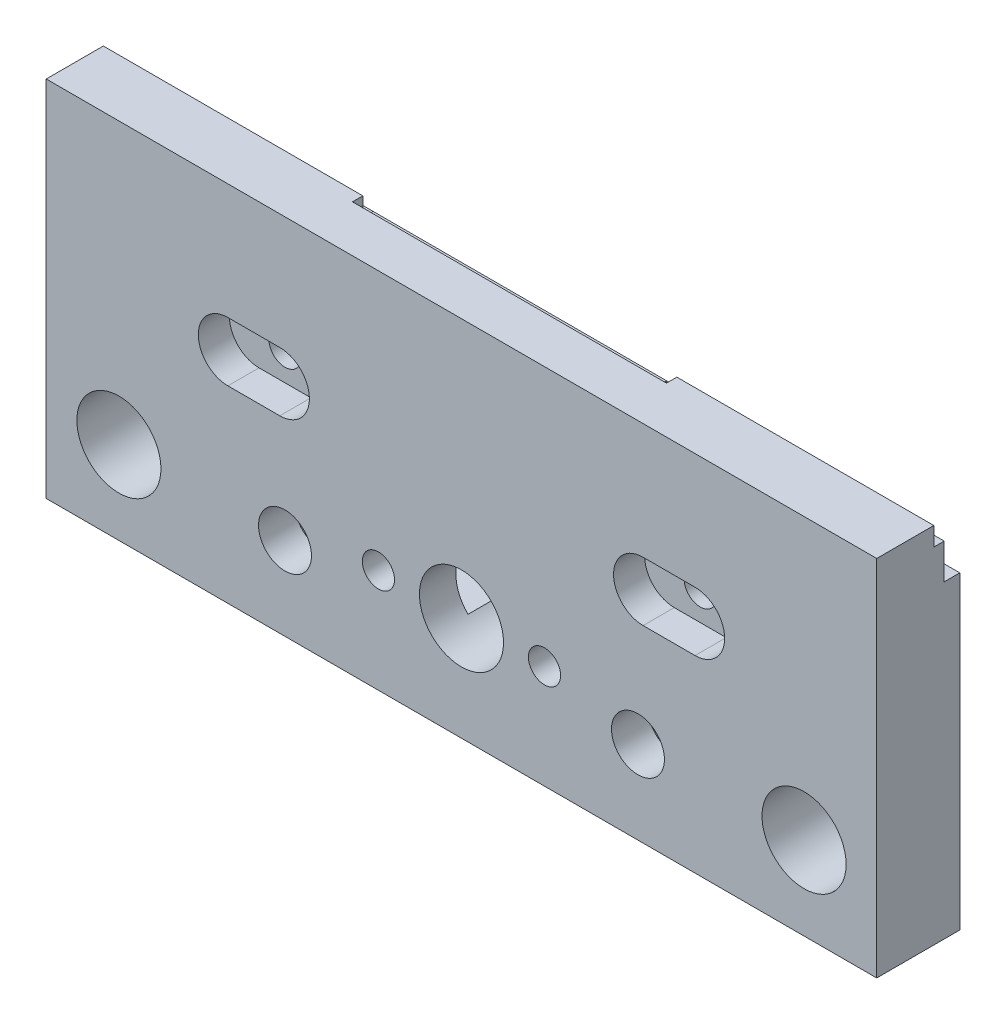
SolidWorks part; units mm, degrees
ref_plane "前视基准面" through (0, 0, 0) normal (0, 0, 1) x (1, 0, 0)
ref_plane "上视基准面" through (0, 0, 0) normal (0, 1, 0) x (1, 0, 0)
ref_plane "右视基准面" through (0, 0, 0) normal (1, 0, 0) x (0, 0, -1)
sketch "前视图草图" plane through (0, 0, 0) normal (0, 0, 1) x (1, 0, 0)
  line L0 (0, 0) -> (44.4821, 0) construction
  line L1 (0, 0) -> (0, 28.3185) construction
sketch "草图2" plane through (0, 0, 0) normal (0, 0, 1) x (1, 0, 0)
  line L0 (0, 0) -> (80, 0)
  line L1 (-200000, 0) -> (200044.4821, 0) construction
  line L2 (80, 0) -> (80, 35)
  line L3 (80, 35) -> (0, 35)
  line L4 (0, -200000) -> (0, 200028.3185) construction
  line L5 (0, 35) -> (0, 0)
  circle A0 centre (7, 8) radius 4.05
  circle A1 centre (40, 10) radius 4.05
  circle A2 centre (73, 8) radius 4.05
  dimension "D3" = 8
  dimension "D5" = 10
  dimension "D9" = 8.1
  dimension "D10" = 8.1
  dimension "D11" = 8.1
  dimension "D1" = 35
  dimension "D2" = 80
  dimension "D4" = 7
  dimension "D6" = 7
  dimension "D7" = 8
  dimension "D8" = 40
extrude "凸台-拉伸1" add sketch "草图2" along normal blind 8
sketch "草图3" plane through (0, 0, 8) normal (0, 0, 1) x (1, 0, 0)
  line L0 (16.088, 8) -> (31.4805, 8) construction
  line L1 (7, 8) -> (7, 16.8386) construction
  line L2 (73, 8) -> (73, 16.5917) construction
  line L4 (-200000, 0) -> (200044.4821, 0) construction
  circle A2 centre (23, 8) radius 2.55
  circle A3 centre (57, 8) radius 2.55
  dimension "D4" = 5.1
  dimension "D5" = 5.1
  dimension "D1" = 8
  dimension "D2" = 16
  dimension "D3" = 16
extrude "切除-拉伸1" cut sketch "草图3" against normal through all
sketch "草图4" plane through (80, 0, 0) normal (1, 0, 0) x (0, 0, -1)
  line L1 (0, -200000) -> (0, 200028.3185) construction
  line L2 (-1.5, 33.2) -> (-2.5, 33.2)
  line L3 (-2.5, 33.2) -> (-2.5, 35)
  line L4 (-8, 35) -> (0, 35) construction
  line L5 (-2.5, 35) -> (0, 35)
  line L6 (-1.5, 33.2) -> (-1.5, 29.8)
  line L7 (-1.5, 29.8) -> (0, 29.8)
  line L8 (0, 29.8) -> (0, 35)
  dimension "D1" = 3.4
  dimension "D2" = 2.5
  dimension "D3" = 1.5
  dimension "D4" = 1.8
extrude "切除-拉伸2" cut sketch "草图4" against normal through all
sketch "草图5" plane through (0, 0, 8) normal (0, 0, 1) x (1, 0, 0)
  line L0 (40, 10) -> (56.5376, 10) construction
  circle A0 centre (40, 10) radius 8 construction
  circle A1 centre (48, 10) radius 1.55
  circle A2 centre (32, 10) radius 1.55
  dimension "D1" = 3.1
  dimension "D2" = 3.1
  dimension "D3" = 16
extrude "切除-拉伸3" cut sketch "草图5" against normal through all
sketch "草图7" plane through (0, 0, 0) normal (0, 0, -1) x (-1, 0, 0)
  line L0 (-40, 12) -> (-40, -8.3696) construction
  line L1 (-23, 10) -> (-23, -2.3368) construction
  line L2 (200000, 0) -> (-200044.4821, 0) construction
  line L6 (-27.05, 10) -> (-27.05, 2.5)
  line L7 (-29.55, 0) -> (-16.45, 0)
  line L8 (-18.95, 2.5) -> (-18.95, 10)
  line L9 (-23, 8) -> (-23, 15.9045) construction
  line L13 (0, -200000) -> (0, 200028.3185) construction
  line L14 (-57, 8) -> (-57, 15.9045) construction
  line L15 (-57, 10) -> (-57, -2.3368) construction
  line L16 (-61.05, 2.5) -> (-61.05, 10)
  line L17 (-50.45, 0) -> (-63.55, 0)
  line L18 (-52.95, 10) -> (-52.95, 2.5)
  arc A1 (-18.95, 10) -> (-27.05, 10) centre (-23, 10) ccw
  arc A4 (-29.55, 0) -> (-27.05, 2.5) centre (-29.55, 2.5) ccw
  arc A5 (-18.95, 2.5) -> (-16.45, 0) centre (-16.45, 2.5) ccw
  arc A7 (-61.05, 2.5) -> (-63.55, 0) centre (-63.55, 2.5) cw
  arc A8 (-50.45, 0) -> (-52.95, 2.5) centre (-50.45, 2.5) cw
  arc A9 (-61.05, 10) -> (-52.95, 10) centre (-57, 10) cw
  dimension "D1" = 40
  dimension "D4" = 8.1
  dimension "D7" = 2.5
  dimension "D8" = 2.5
  dimension "D3" = 10
extrude "切除-拉伸4" cut sketch "草图7" against normal blind 4.5
sketch "草图8" plane through (0, 0, 0) normal (0, 0, -1) x (-1, 0, 0)
  line L0 (-40, 10) -> (-57.3165, 10) construction
  line L1 (-40, 20) -> (-40, 35.6562) construction
  line L2 (-30.5, 12.85) -> (-49.5, 12.85)
  line L3 (-49.5, 7.15) -> (-30.5, 7.15)
  line L4 (200000, 0) -> (-200044.4821, 0) construction
  arc A0 (-30.5, 7.15) -> (-30.5, 12.85) centre (-30.5, 10) ccw
  arc A1 (-49.5, 12.85) -> (-49.5, 7.15) centre (-49.5, 10) ccw
  dimension "D1" = 5.7
  dimension "D2" = 9.5
  dimension "D3" = 9.5
  dimension "D4" = 10
extrude "切除-拉伸5" cut sketch "草图8" against normal blind 4.5
sketch "草图11" plane through (0, 0, 0) normal (0, 0, -1) x (-1, 0, 0)
  line L0 (-40, 20) -> (-58.6363, 20) construction
  line L1 (-80, 0) -> (-80, 29.8) construction
  line L2 (0, -200000) -> (0, 200028.3185) construction
  line L3 (-40, 20) -> (-40, 13.5744) construction
  line L4 (-28.772, 21) -> (-45.9396, 21) construction
  circle A0 centre (-60, 21) radius 1.55
  circle A1 centre (-20, 21) radius 1.55
  point P23 (-40, 20)
  dimension "D1" = 3.1
  dimension "D2" = 3.1
  dimension "D3" = 20
  dimension "D4" = 20
  dimension "D5" = 1
extrude "切除-拉伸7" cut sketch "草图11" against normal through all contours A0 | A1
sketch "草图12" plane through (0, 0, 0) normal (0, 0, -1) x (-1, 0, 0)
  line L0 (-62.5, 18.15) -> (-57.5, 18.15)
  line L1 (-57.5, 23.85) -> (-62.5, 23.85)
  line L4 (-40, 20) -> (-42.9914, 20) construction
  line L5 (-39.1423, 21) -> (-43.2672, 21) construction
  line L6 (-60, 21) -> (-60, 25.2385) construction
  line L7 (-20, 21) -> (-20, 26.1603) construction
  line L8 (-40, 20) -> (-40, 24.3689) construction
  line L9 (-17.5, 23.85) -> (-22.5, 23.85)
  line L10 (-22.5, 18.15) -> (-17.5, 18.15)
  arc A0 (-62.5, 23.85) -> (-62.5, 18.15) centre (-62.5, 21) ccw
  arc A1 (-57.5, 18.15) -> (-57.5, 23.85) centre (-57.5, 21) ccw
  arc A4 (-17.5, 18.15) -> (-17.5, 23.85) centre (-17.5, 21) ccw
  arc A5 (-22.5, 23.85) -> (-22.5, 18.15) centre (-22.5, 21) ccw
  point P16 (-38, 21)
  point P28 (-40, 21)
  dimension "D2" = 1
  dimension "D3" = 5
  dimension "D4" = 2.5
  dimension "D1" = 2
extrude "切除-拉伸8" cut sketch "草图12" against normal blind 3
sketch "草图15" plane through (0, 0, 8) normal (0, 0, 1) x (1, 0, 0)
  line L2 (57.5, 18.15) -> (62.5, 18.15)
  line L3 (62.5, 23.85) -> (57.5, 23.85)
  line L4 (57.5, 18.15) -> (62.5, 18.15)
  line L5 (62.5, 23.85) -> (57.5, 23.85)
  line L6 (22.5, 23.85) -> (17.5, 23.85)
  line L7 (17.5, 18.15) -> (22.5, 18.15)
  line L8 (22.5, 23.85) -> (17.5, 23.85)
  line L9 (17.5, 18.15) -> (22.5, 18.15)
  arc A2 (62.5, 18.15) -> (62.5, 23.85) centre (62.5, 21) ccw
  arc A3 (57.5, 23.85) -> (57.5, 18.15) centre (57.5, 21) ccw
  arc A4 (62.5, 18.15) -> (62.5, 23.85) centre (62.5, 21) ccw
  arc A5 (57.5, 23.85) -> (57.5, 18.15) centre (57.5, 21) ccw
  arc A6 (17.5, 23.85) -> (17.5, 18.15) centre (17.5, 21) ccw
  arc A7 (22.5, 18.15) -> (22.5, 23.85) centre (22.5, 21) ccw
  arc A8 (17.5, 23.85) -> (17.5, 18.15) centre (17.5, 21) ccw
  arc A9 (22.5, 18.15) -> (22.5, 23.85) centre (22.5, 21) ccw
  dimension "D1" = 0
  dimension "D2" = 0
extrude "切除-拉伸9" cut sketch "草图15" against normal blind 3
sketch "草图19" plane through (0, 0, 2.5) normal (0, 0, -1) x (-1, 0, 0)
  line L0 (0, 35) -> (-80, 35) construction
  line L1 (-25, 35) -> (-55.2479, 35)
  line L2 (-25, 35) -> (-25, 34.2)
  line L3 (-26, 34.2) -> (-54.2479, 34.2)
  line L4 (-55.2479, 35) -> (-55.2479, 34.2)
  line L5 (0, -200000) -> (0, 200028.3185) construction
  line L7 (0, 33.2) -> (-80, 33.2) construction
  line L8 (-56.3335, 33.7) -> (-52.9089, 33.7) construction
  line L9 (-55.2479, 1028.5823) -> (-55.2479, 34.2) construction
  line L10 (-25, 1028.5823) -> (-25, 33.7) construction
  line L11 (-55.2479, 33.7) -> (-55.2479, -973.3) construction
  line L12 (-25, 33.7) -> (-25, -973.3) construction
  arc A3 (-55.2479, 34.2) -> (-54.2479, 34.2) centre (-54.7479, 34.2) ccw
  arc A6 (-26, 34.2) -> (-25, 34.2) centre (-25.5, 34.2) ccw
  dimension "D3" = 1
  dimension "D4" = 1
  dimension "D2" = 0.8
  dimension "D1" = 0.5
  dimension "D9" = 25
extrude "切除-拉伸11" cut sketch "草图19" against normal mid plane 2
